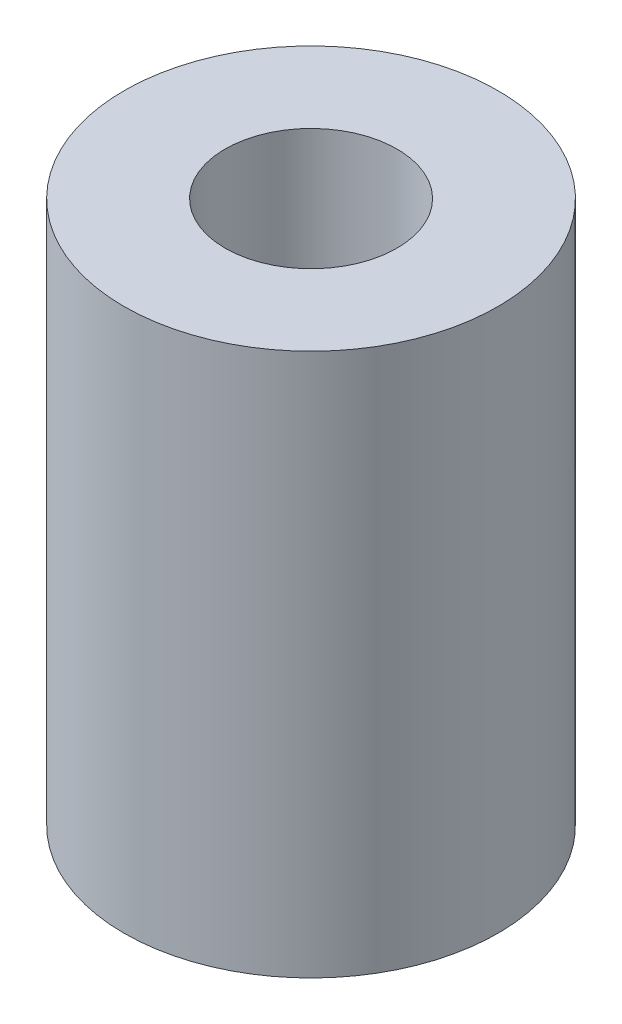
SolidWorks part; units mm, degrees
ref_plane "Front Plane" through (0, 0, 0) normal (0, 0, 1) x (1, 0, 0)
ref_plane "Top Plane" through (0, 0, 0) normal (0, 1, 0) x (1, 0, 0)
ref_plane "Right Plane" through (0, 0, 0) normal (1, 0, 0) x (0, 0, -1)
sketch "Sketch1" plane through (0, 0, 0) normal (0, 1, 0) x (1, 0, 0)
  circle A0 centre (0, 0) radius 3.1
  circle A1 centre (0, 0) radius 1.425
  dimension "D1" = 6.2
  dimension "D2" = 2.85
extrude "Boss-Extrude1" add sketch "Sketch1" along normal blind 9
